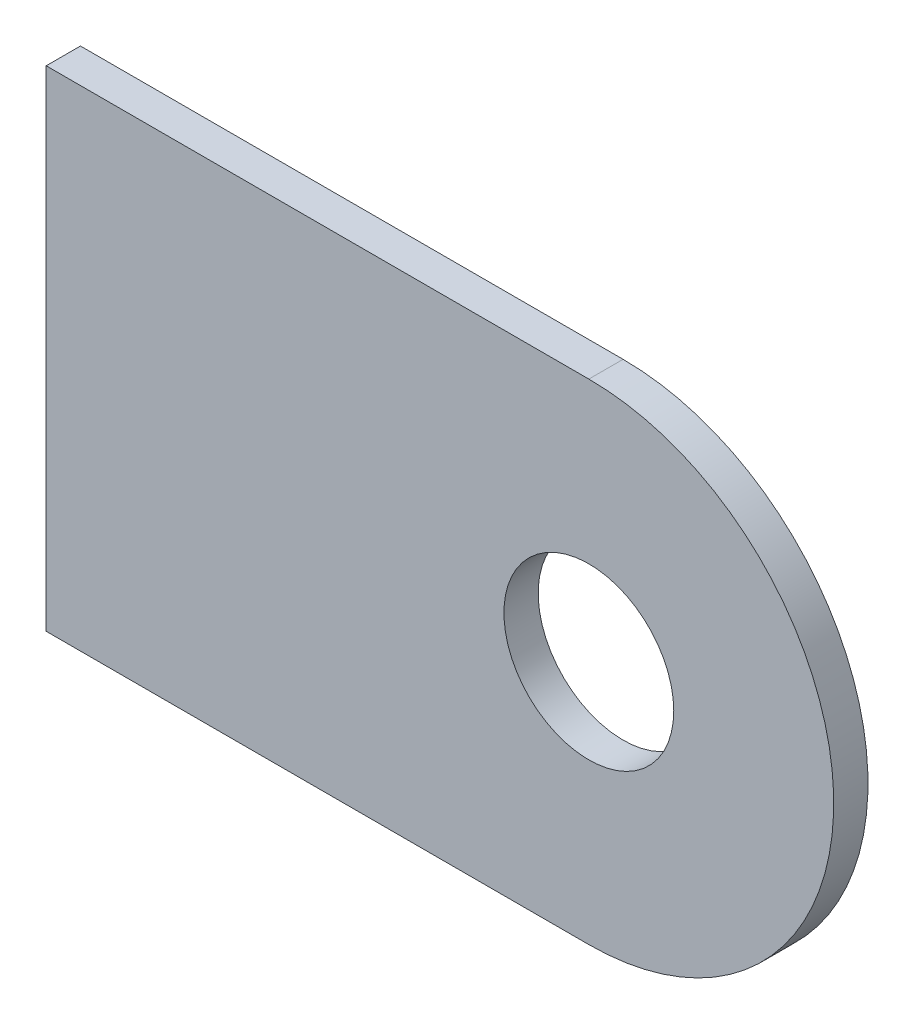
SolidWorks part; units mm, degrees
ref_plane "Front Plane" through (0, 0, 0) normal (0, 0, 1) x (1, 0, 0)
ref_plane "Top Plane" through (0, 0, 0) normal (0, 1, 0) x (1, 0, 0)
ref_plane "Right Plane" through (0, 0, 0) normal (1, 0, 0) x (0, 0, -1)
sketch "Sketch2" plane through (0, 0, 0) normal (0, 0, 1) x (1, 0, 0)
  line L1 (0, 0) -> (25.1587, 0)
  line L2 (0, 0) -> (0, 22.7076)
  line L3 (0, 22.7076) -> (25.1587, 22.7076)
  arc A0 (25.1587, 0) -> (25.1587, 22.7076) centre (25.1587, 11.3538) ccw
  circle A1 centre (25.1587, 11.3538) radius 3.937
  point P7 (36.5125, 11.3538)
  dimension "D3" = 7.874
  dimension "D1" = 36.5125
  dimension "D2" = 22.7076
extrude "Boss-Extrude1" add sketch "Sketch2" along normal blind 1.5875
